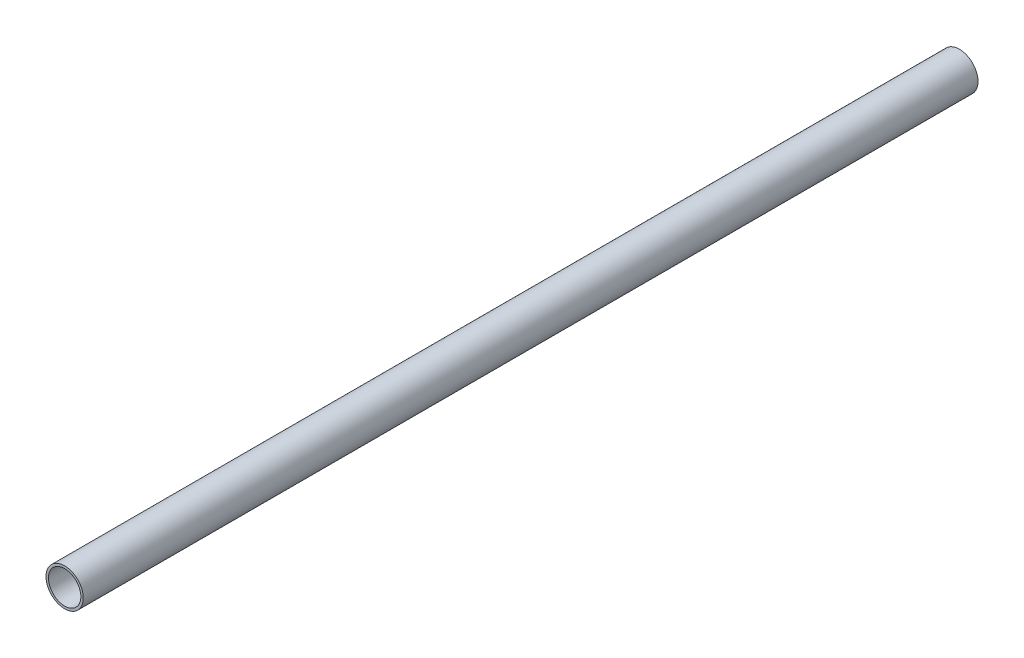
SolidWorks part; units mm, degrees
material "Acrylic (Medium-high impact)"
ref_plane "Front Plane" through (0, 0, 0) normal (0, 0, 1) x (1, 0, 0)
ref_plane "Top Plane" through (0, 0, 0) normal (0, 1, 0) x (1, 0, 0)
ref_plane "Right Plane" through (0, 0, 0) normal (1, 0, 0) x (0, 0, -1)
sketch "Sketch1" plane through (0, 0, 0) normal (0, 0, 1) x (1, 0, 0)
  circle A0 centre (0, 0) radius 12.7
  circle A1 centre (0, 0) radius 11.049
  dimension "D1" = 25.4
  dimension "D2" = 22.098
extrude "Boss-Extrude1" add sketch "Sketch1" along normal blind 609.6
sketch "Sketch2" plane through (0, 0, 0) normal (0, 0, 1) x (1, 0, 0)
  circle A0 centre (0, 0) radius 11.0998
  circle A1 centre (0, 0) radius 11.049
  dimension "D1" = 22.1996
  dimension "D2" = 22.098
extrude "Cut-Extrude1" cut sketch "Sketch2" along normal blind 50.8
